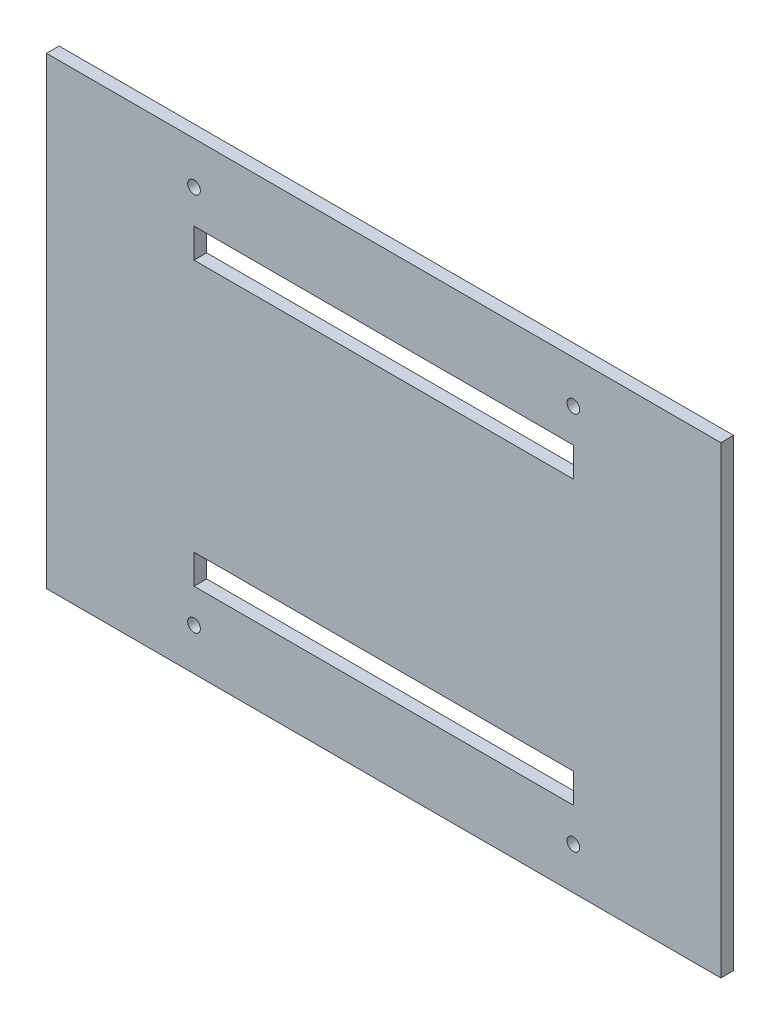
SolidWorks part; units mm, degrees
ref_plane "Front Plane" through (0, 0, 0) normal (0, 0, 1) x (1, 0, 0)
ref_plane "Top Plane" through (0, 0, 0) normal (0, 1, 0) x (1, 0, 0)
ref_plane "Right Plane" through (0, 0, 0) normal (1, 0, 0) x (0, 0, -1)
sketch "Sketch1" plane through (0, 0, 0) normal (0, 0, 1) x (1, 0, 0)
  line L1 (-80, 55) -> (80, 55)
  line L2 (-80, 55) -> (-80, -55)
  line L3 (-80, -55) -> (80, -55)
  line L4 (80, 55) -> (80, -55)
  line L5 (-80, 55) -> (80, -55) construction
  line L6 (-80, -55) -> (80, 55) construction
  line L7 (-45, 45) -> (45, 45) construction
  line L8 (-45, 45) -> (-45, -45) construction
  line L9 (-45, -45) -> (45, -45) construction
  line L10 (45, 45) -> (45, -45) construction
  line L11 (-45, 45) -> (45, -45) construction
  line L12 (-45, -45) -> (45, 45) construction
  line L13 (-45, 37) -> (45, 37)
  line L14 (-45, 37) -> (-45, 30)
  line L15 (-45, 30) -> (45, 30)
  line L16 (45, 37) -> (45, 30)
  line L17 (-45, -30) -> (45, -30)
  line L18 (-45, -30) -> (-45, -37)
  line L19 (-45, -37) -> (45, -37)
  line L20 (45, -30) -> (45, -37)
  circle A0 centre (45, 45) radius 1.5
  circle A1 centre (-45, 45) radius 1.5
  circle A2 centre (-45, -45) radius 1.5
  circle A3 centre (45, -45) radius 1.5
  point P0 (0, 0)
  point P6 (0, 0)
  dimension "D5" = 3
  dimension "D1" = 160
  dimension "D2" = 110
  dimension "D3" = 90
  dimension "D4" = 90
  dimension "D6" = 60
  dimension "D7" = 7
  dimension "D8" = 7
  dimension "D9" = 30
extrude "Boss-Extrude1" add sketch "Sketch1" along normal blind 3
